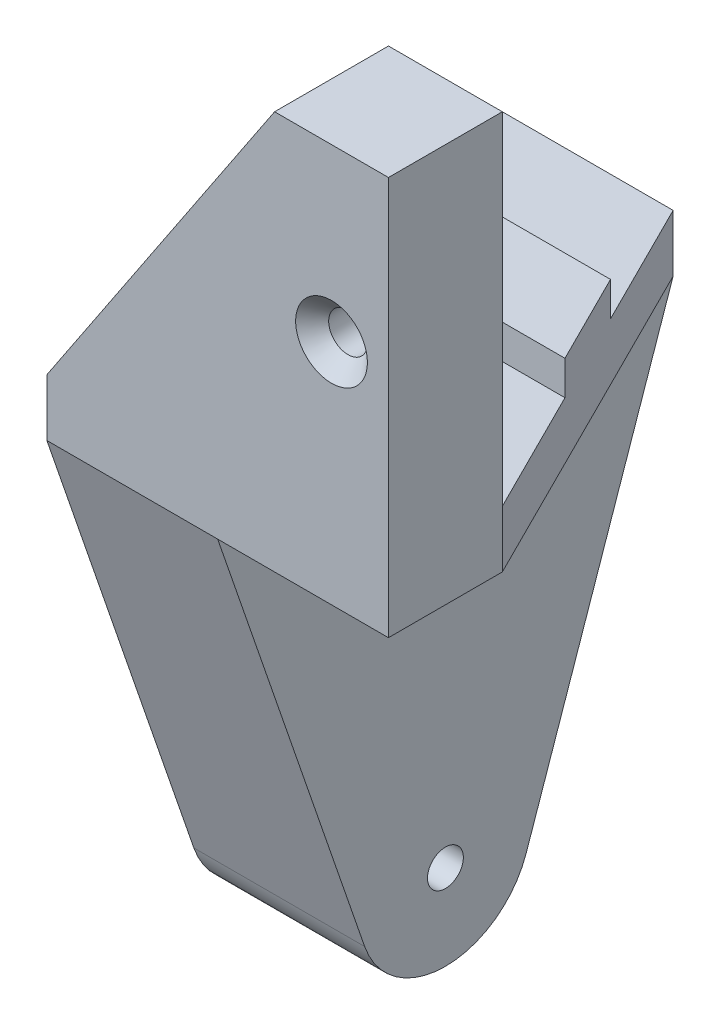
SolidWorks part; units mm, degrees
ref_plane "前视基准面" through (0, 0, 0) normal (0, 0, 1) x (1, 0, 0)
ref_plane "上视基准面" through (0, 0, 0) normal (0, 1, 0) x (1, 0, 0)
ref_plane "右视基准面" through (0, 0, 0) normal (1, 0, 0) x (0, 0, -1)
other "Configuration Table"
sketch "草图1" plane through (0, 0, 0) normal (0, 0, 1) x (1, 0, 0)
  line L0 (0, 0) -> (20, 30)
  line L1 (0, 0) -> (30, 0)
  line L3 (20, 30) -> (30, 30)
  line L4 (30, 0) -> (30, 30)
  point P2 (25, 15)
  point P7 (30, 15)
  point P9 (25, 30)
  dimension "D1" = 30
  dimension "D2" = 30
  dimension "D3" = 10
extrude "凸台-拉伸1" add sketch "草图1" along normal blind 10
sketch "草图2" plane through (0, 0, 0) normal (0, -1, 0) x (1, 0, 0)
  line L0 (30, 10) -> (30, 0) construction
  line L1 (0, 10) -> (30, 10)
  line L2 (0, 10) -> (0, -30)
  line L3 (0, -30) -> (15, -30)
  line L4 (30, 10) -> (30, 0)
  line L5 (15, -30) -> (30, 0)
  dimension "D1" = 30
  dimension "D2" = 15
extrude "凸台-拉伸2" add sketch "草图2" along normal blind 5
sketch "草图3" plane through (0, 0, 0) normal (-1, 0, 0) x (0, 0, 1)
  line L0 (-30, -5) -> (-17.0904, -42.4445)
  line L1 (10, -5) -> (-2.9096, -42.4445)
  line L2 (10, -5) -> (-30, -5) construction
  line L3 (0, 0) -> (-30, 0) construction
  line L4 (-30, -5) -> (10, -5)
  arc A0 (-17.0904, -42.4445) -> (-2.9096, -42.4445) centre (-10, -40) ccw
  point P11 (-10, -5)
  dimension "D1" = 15
  dimension "D2" = 40
extrude "凸台-拉伸3" add sketch "草图3" against normal blind 15
sketch "草图4" plane through (0, 0, 0) normal (0, 1, 0) x (1, 0, 0)
  line L0 (0, 0) -> (0, 30) construction
  line L1 (0, 11) -> (24.5, 11)
  line L2 (0, 11) -> (0, 19)
  line L3 (0, 19) -> (20.5, 19)
  line L5 (20.5, 19) -> (24.5, 11)
  line L6 (15, 30) -> (30, 0) construction
  line L7 (20, 0) -> (0, 0) construction
  point P1 (0, 15)
  dimension "D1" = 8
  dimension "D2" = 15
extrude "凸台-拉伸4" add sketch "草图4" along normal blind 3
hole_wizard "M3 平头机械螺钉的锥形沉头孔1" positions "草图5" profile "草图6" countersink size "M3" standard "ANSI Metric" end condition up to next
sketch "草图5" plane through (0, 0, 10) normal (0, 0, 1) x (1, 0, 0)
  point P0 (25, 15)
sketch "草图6" plane through (25, 15, 10) normal (1, 0, 0) x (0, -1, 0)
  line L0 (0, 0) -> (0, 10)
  line L1 (0, 10) -> (1.7, 10)
  line L2 (1.7, 10) -> (1.7, 1.45)
  line L3 (1.7, 1.45) -> (3.15, 0)
  line L5 (3.15, 0) -> (0, 0)
  line L6 (-1.7, 1.45) -> (-3.15, 0) construction
  line L11 (0, -6.35) -> (0, 107.95) construction
  dimension "通孔孔直径" = 3.4
  dimension "通孔孔深度" = 10
  dimension "近端锥形沉头孔直径" = 6.3
  dimension "近端锥形沉头孔角度" = 90
hole_wizard "M3 螺旋的螺纹孔钻头1" positions "草图7" profile "草图8" hole size "M3x0.5" standard "ANSI Metric" end condition up to next
sketch "草图7" plane through (0, 0, 0) normal (-1, 0, 0) x (0, 0, 1)
  point P0 (-10, -40)
sketch "草图8" plane through (0, -40, -10) normal (0, 1, 0) x (0, 0, 1)
  line L0 (0, 0) -> (0, 15)
  line L1 (0, 15) -> (1.575, 15)
  line L2 (1.575, 15) -> (1.575, 0)
  line L5 (1.575, 0) -> (0, 0)
  line L11 (0, -6.35) -> (0, 107.95) construction
  dimension "通孔孔直径" = 3.15
  dimension "通孔孔深度" = 15
